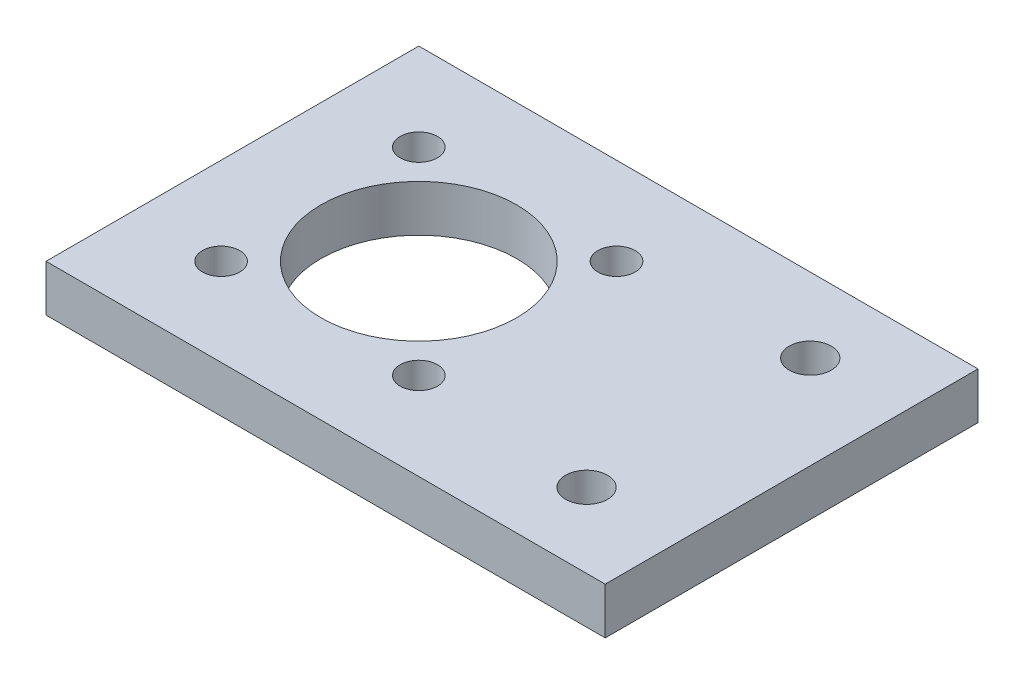
SolidWorks part; units mm, degrees
ref_plane "Front Plane" through (0, 0, 0) normal (0, 0, 1) x (1, 0, 0)
ref_plane "Top Plane" through (0, 0, 0) normal (0, 1, 0) x (1, 0, 0)
ref_plane "Right Plane" through (0, 0, 0) normal (1, 0, 0) x (0, 0, -1)
sketch "Sketch1" plane through (0, 0, 0) normal (0, 1, 0) x (1, 0, 0)
  line L1 (-30, -20) -> (30, -20)
  line L2 (-30, -20) -> (-30, 20)
  line L3 (-30, 20) -> (30, 20)
  line L4 (30, -20) -> (30, 20)
  line L5 (-30, -20) -> (30, 20) construction
  line L6 (-30, 20) -> (30, -20) construction
  point P0 (0, 0)
  dimension "D1" = 60
  dimension "D2" = 40
extrude "Boss-Extrude1" add sketch "Sketch1" along normal blind 5
sketch "Sketch4" plane through (0, 5, 0) normal (0, 1, 0) x (1, 0, 0)
  line L0 (30, -20) -> (30, 20) construction
  circle A0 centre (20, 12) radius 2.25
  circle A1 centre (20, -12) radius 2.25
  dimension "D1" = 4.5
  dimension "D2" = 4.5
  dimension "D4" = 10
  dimension "D3" = 10
extrude "Cut-Extrude2" cut sketch "Sketch4" against normal through all
sketch "Sketch6" plane through (0, 5, 0) normal (0, 1, 0) x (1, 0, 0)
  line L0 (0.6065, 10.6065) -> (0.6065, -10.6067) construction
  line L1 (0.6065, -10.6067) -> (-20.6067, -10.6067) construction
  line L2 (-30, 0) -> (30, 0) construction
  line L3 (-30, 20) -> (-30, -20) construction
  line L4 (30, -20) -> (30, 20) construction
  line L5 (-30, 20) -> (-10, 20) construction
  line L7 (30, 20) -> (-30, 20) construction
  line L9 (-10, 20) -> (-10, -20) construction
  line L10 (-30, -20) -> (30, -20) construction
  circle A0 centre (-10.0001, -0.0001) radius 10.5
  circle A1 centre (-20.6067, 10.6065) radius 2
  circle A2 centre (0.6065, 10.6065) radius 2
  circle A3 centre (0.6065, -10.6067) radius 2
  circle A4 centre (-20.6067, -10.6067) radius 2
  point P8 (-10.0001, -0.0001)
  point P21 (0, 0)
  point P25 (0, 0)
  dimension "D1" = 20
extrude "Cut-Extrude3" cut sketch "Sketch6" against normal through all
